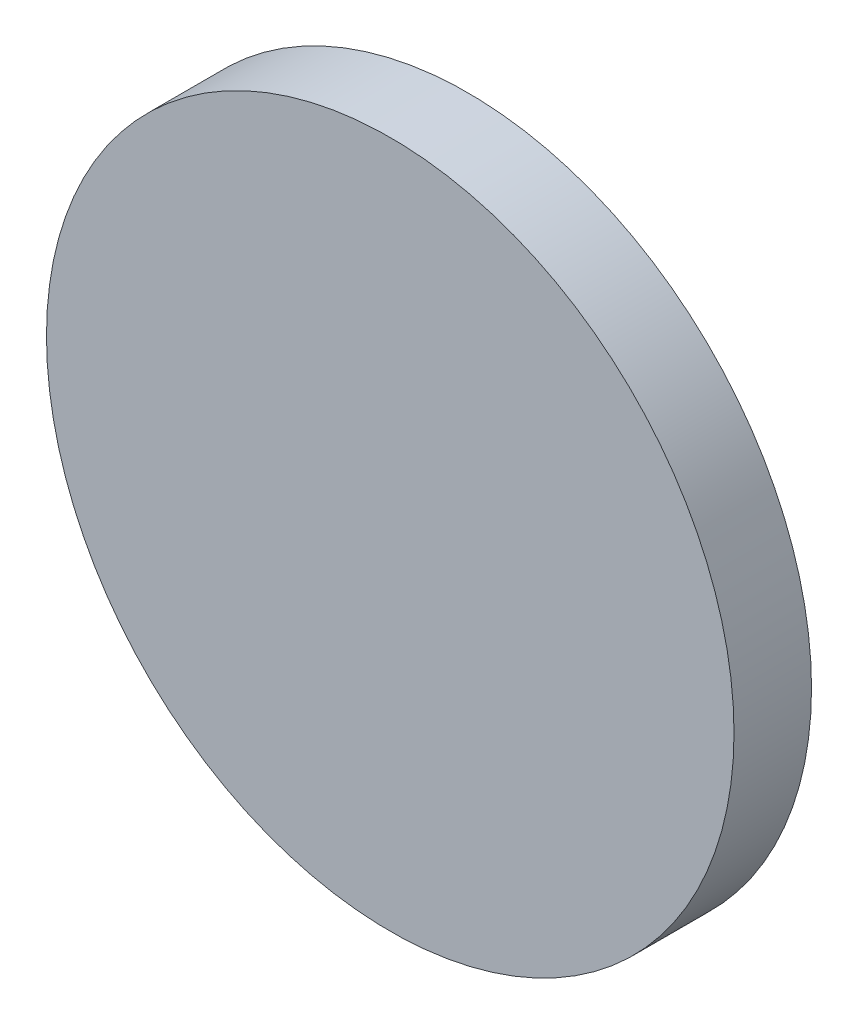
SolidWorks part; units mm, degrees
ref_plane "Front Plane" through (0, 0, 0) normal (0, 0, 1) x (1, 0, 0)
ref_plane "Top Plane" through (0, 0, 0) normal (0, 1, 0) x (1, 0, 0)
ref_plane "Right Plane" through (0, 0, 0) normal (1, 0, 0) x (0, 0, -1)
sketch "Sketch1" plane through (0, 0, 0) normal (0, 0, 1) x (1, 0, 0)
  circle A0 centre (0, 0) radius 28.1626
extrude "Boss-Extrude1" add sketch "Sketch1" along normal blind 6.35
